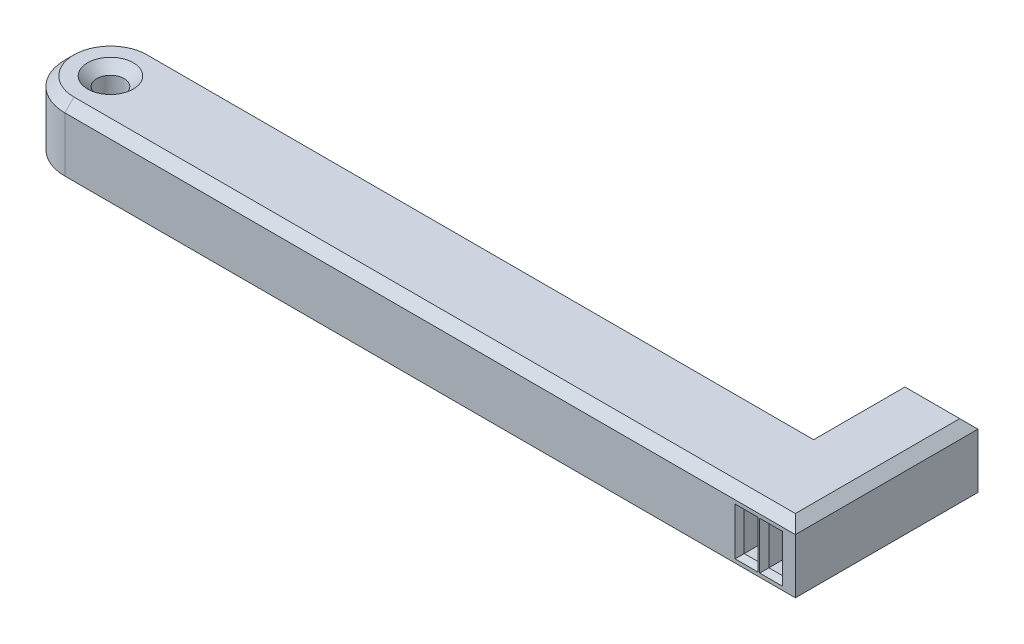
SolidWorks part; units mm, degrees
ref_plane "Front Plane" through (0, 0, 0) normal (0, 0, 1) x (1, 0, 0)
ref_plane "Top Plane" through (0, 0, 0) normal (0, 1, 0) x (1, 0, 0)
ref_plane "Right Plane" through (0, 0, 0) normal (1, 0, 0) x (0, 0, -1)
sketch "Sketch1" plane through (0, 0, 0) normal (0, 1, 0) x (1, 0, 0)
  line L0 (0, 5) -> (80, 5)
  line L1 (80, 5) -> (80, -5)
  line L2 (80, -5) -> (0, -5)
  line L4 (80, 5) -> (72, 5)
  line L5 (80, 5) -> (80, 15)
  line L6 (80, 15) -> (72, 15)
  line L7 (72, 5) -> (72, 15)
  circle A0 centre (0, 0) radius 5
  circle A1 centre (0, 0) radius 1.5
  dimension "D1" = 3
  dimension "D2" = 10
  dimension "D3" = 80
  dimension "D4" = 8
  dimension "D5" = 10
extrude "Boss-Extrude1" add sketch "Sketch1" along normal blind 8 contours A0 L2 L1 L0 | L7 L0 L5 L6 | A0 A1
sketch "Sketch2" plane through (0, 0, -15) normal (0, 0, -1) x (-1, 0, 0)
  line L8 (-78.1, 1.9) -> (-73.9, 1.9)
  line L9 (-73.9, 1.9) -> (-73.9, 6.1)
  line L10 (-73.9, 6.1) -> (-78.1, 6.1)
  line L11 (-78.1, 6.1) -> (-78.1, 1.9)
  line L12 (-78.1, 1.9) -> (-73.9, 1.9)
  line L13 (-73.9, 1.9) -> (-73.9, 6.1)
  line L14 (-73.9, 6.1) -> (-78.1, 6.1)
  line L15 (-78.1, 6.1) -> (-78.1, 1.9)
  dimension "D1" = 1.9
extrude "Cut-Extrude1" cut sketch "Sketch2" against normal blind 3.5
sketch "Sketch3" plane through (0, 0, -11.5) normal (0, 0, -1) x (-1, 0, 0)
  line L0 (-78.1, 1.9) -> (-73.9, 1.9) construction
  line L1 (-78.1, 6.1) -> (-76.6, 6.1)
  line L2 (-78.1, 6.1) -> (-78.1, 1.9)
  line L3 (-78.1, 1.9) -> (-76.6, 1.9)
  line L4 (-76.6, 6.1) -> (-76.6, 1.9)
  line L6 (-73.9, 6.1) -> (-75.4, 6.1)
  line L7 (-73.9, 6.1) -> (-73.9, 1.9)
  line L8 (-73.9, 1.9) -> (-75.4, 1.9)
  line L9 (-75.4, 6.1) -> (-75.4, 1.9)
  dimension "D1" = 1.5
  dimension "D2" = 1.5
extrude "Cut-Extrude2" cut sketch "Sketch3" against normal through all
chamfer "Chamfer1" distance 1 angle 45 14 edges at (0, 8, 1.5) (72, 8, -10) (76, 8, -15) (80, 8, -5) (40, 8, 5) (-5, 8, 0) (36, 8, -5) (0, 0, 1.5) (-5, 0, 0) (40, 0, 5) (80, 0, -5) (76, 0, -15) (72, 0, -10) (36, 0, -5)
chamfer "Chamfer2" distance 0.5 angle 45 12 edges at (73.9, 4, -15) (76, 1.9, -15) (78.1, 4, -15) (76, 6.1, -15) (74.65, 6.1, 5) (73.9, 4, 5) (74.65, 1.9, 5) (75.4, 4, 5) (77.35, 6.1, 5) (76.6, 4, 5) (77.35, 1.9, 5) (78.1, 4, 5)
